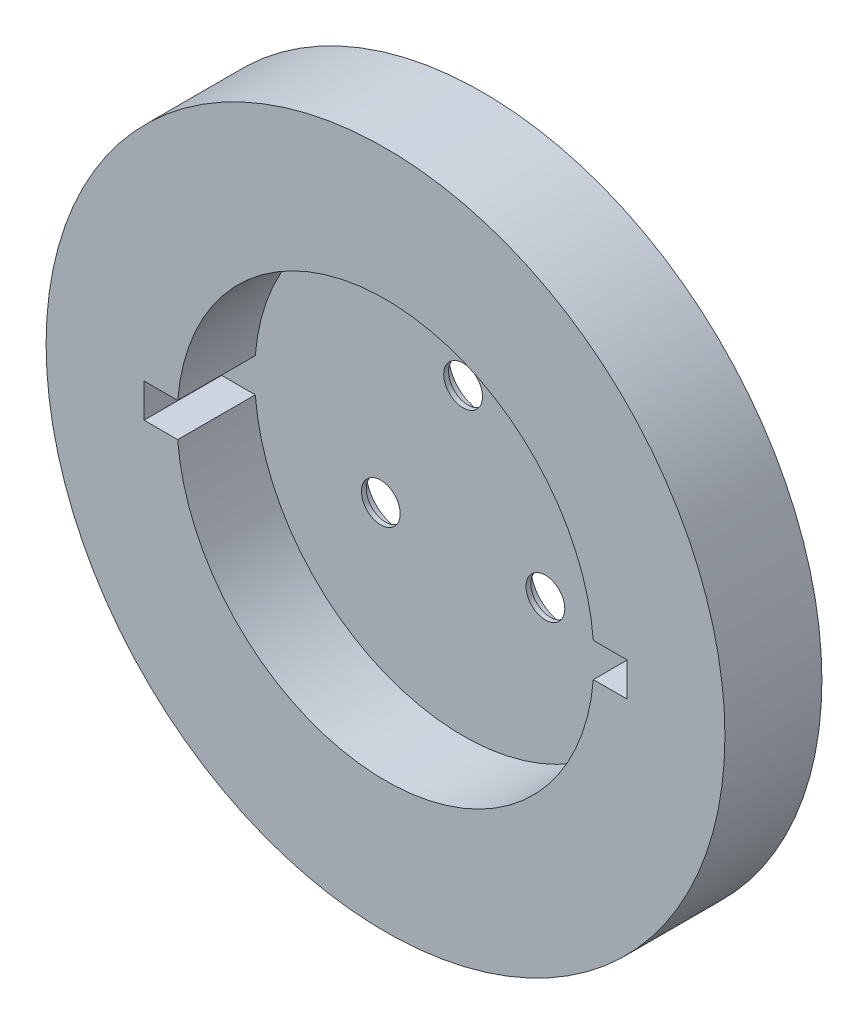
SolidWorks part; units mm, degrees
ref_plane "前视基准面" through (0, 0, 0) normal (0, 0, 1) x (1, 0, 0)
ref_plane "上视基准面" through (0, 0, 0) normal (0, 1, 0) x (1, 0, 0)
ref_plane "右视基准面" through (0, 0, 0) normal (1, 0, 0) x (0, 0, -1)
other "Configuration Table"
sketch "草图1" plane through (0, 0, 0) normal (0, 0, 1) x (1, 0, 0)
  line L0 (0, 0) -> (0, 9.8)
  line L1 (0, 0) -> (-8.487, -4.9)
  line L2 (0, 0) -> (8.487, -4.9)
  circle A0 centre (0, 0) radius 35
  dimension "D1" = 70
  dimension "D2" = 9.8
  dimension "D3" = 120
  dimension "D4" = 9.8
  dimension "D5" = 9.8
  dimension "D6" = 120
extrude "凸台-拉伸1" add sketch "草图1" along normal blind 10
sketch "草图2" plane through (0, 0, 10) normal (0, 0, 1) x (1, 0, 0)
  line L0 (0, 0) -> (24.9, 0) construction
  line L1 (24.9, 0) -> (24.9, 1.75)
  line L2 (24.9, 0) -> (24.9, -1.75)
  line L3 (24.9, 1.75) -> (21.4287, 1.75)
  line L4 (24.9, -1.75) -> (21.4287, -1.75)
  line L5 (-24.9, -1.75) -> (-21.4287, -1.75)
  line L6 (-24.9, 0) -> (-24.9, -1.75)
  line L7 (-24.9, 0) -> (-24.9, 1.75)
  line L8 (-24.9, 1.75) -> (-21.4287, 1.75)
  circle A0 centre (0, 0) radius 21.5
  circle A1 centre (0, 0) radius 17.5
  point P16 (0, 0)
  dimension "D1" = 2
extrude "切除-拉伸1" cut sketch "草图2" against normal blind 8
sketch "草图4" plane through (0, 0, 0) normal (0, 0, -1) x (-1, 0, 0)
  line L0 (0, 0) -> (0, 9.8)
  line L1 (0, 0) -> (8.487, -4.9)
  line L2 (0, 0) -> (-8.487, -4.9)
  circle A0 centre (8.487, -4.9) radius 3.5
  circle A1 centre (-8.487, -4.9) radius 3.5
  circle A2 centre (0, 9.8) radius 3.5
  point P7 (0, 0)
  point P13 (0, 0)
  dimension "D2" = 7
  dimension "D1" = 3
  dimension "D3" = 3
extrude "切除-拉伸2" cut sketch "草图4" against normal blind 1.5
sketch "草图6" plane through (0, 0, 1.5) normal (0, 0, -1) x (-1, 0, 0)
  line L0 (0, 0) -> (0, 9.8)
  circle A0 centre (0, 9.8) radius 2
  circle A1 centre (8.487, -4.9) radius 2
  circle A2 centre (-8.487, -4.9) radius 2
  point P11 (0, 0)
  dimension "D1" = 3
extrude "切除-拉伸3" cut sketch "草图6" against normal through all
